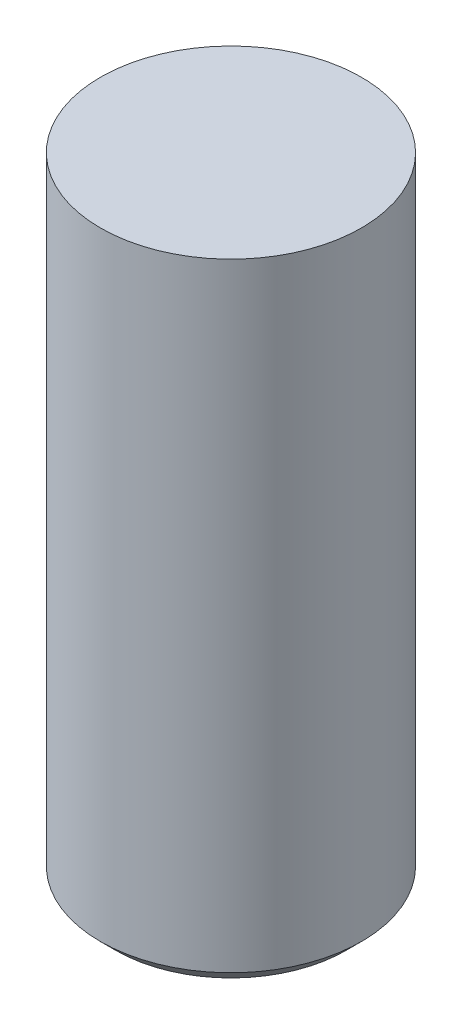
SolidWorks part; units mm, degrees
ref_plane "Front Plane" through (0, 0, 0) normal (0, 0, 1) x (1, 0, 0)
ref_plane "Top Plane" through (0, 0, 0) normal (0, 1, 0) x (1, 0, 0)
ref_plane "Right Plane" through (0, 0, 0) normal (1, 0, 0) x (0, 0, -1)
sketch "Sketch1" plane through (0, 0, 0) normal (0, 1, 0) x (1, 0, 0)
  circle A0 centre (0, 0) radius 16.9
  dimension "D1" = 33.8
extrude "Boss-Extrude1" add sketch "Sketch1" along normal mid plane 82
chamfer "Chamfer1" distance 2 angle 45 1 edges at (0, -41, 16.9)
